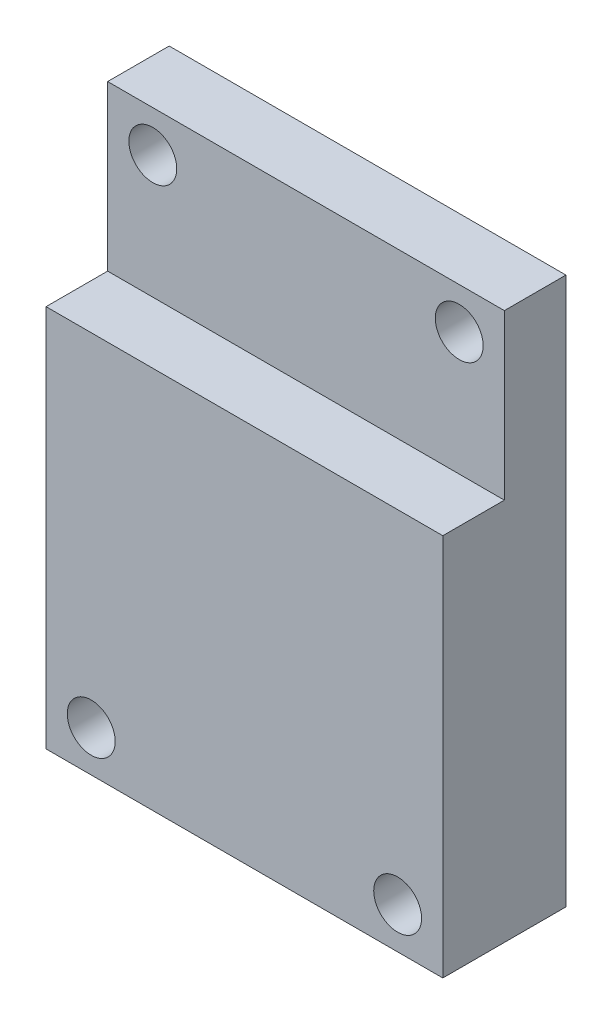
SolidWorks part; units mm, degrees
ref_plane "정면" through (0, 0, 0) normal (0, 0, 1) x (1, 0, 0)
ref_plane "윗면" through (0, 0, 0) normal (0, 1, 0) x (1, 0, 0)
ref_plane "우측면" through (0, 0, 0) normal (1, 0, 0) x (0, 0, -1)
sketch "스케치1" plane through (0, 0, 0) normal (0, 0, 1) x (1, 0, 0)
  line L2 (14.5, -20) -> (-14.5, -20)
  line L3 (14.5, -20) -> (14.5, 20)
  line L4 (14.5, 20) -> (-14.5, 20)
  line L5 (-14.5, -20) -> (-14.5, 20)
  line L6 (14.5, -20) -> (-14.5, 20) construction
  line L7 (14.5, 20) -> (-14.5, -20) construction
  line L9 (-14.5, 17) -> (14.5, 17) construction
  line L10 (-14.5, 0) -> (14.5, 0) construction
  circle A0 centre (11.1994, 17) radius 1.75
  circle A1 centre (-11.1994, 17) radius 1.75
  circle A2 centre (11.1994, -17) radius 1.75
  circle A6 centre (-11.1994, -17) radius 1.75
  point P3 (0, 0)
  dimension "D3" = 40
  dimension "D1" = 3
extrude "보스-돌출1" add sketch "스케치1" along normal blind 9
ref_plane "평면1" through (0, 0, 2) normal (0, 0, 1) x (1, 0, 0)
ref_plane "평면2" through (0, 0, 4.5) normal (0, 0, -1) x (-1, 0, 0)
sketch "스케치3" plane through (0, 0, 4.5) normal (0, 0, -1) x (-1, 0, 0)
  line L0 (14.5, 20) -> (14.5, -20) construction
  line L1 (-14.5, 20) -> (14.5, 20)
  line L2 (-14.5, 20) -> (-14.5, 8)
  line L3 (-14.5, 8) -> (14.5, 8)
  line L4 (14.5, 20) -> (14.5, 8)
extrude "컷-돌출2" cut sketch "스케치3" against normal blind 5
